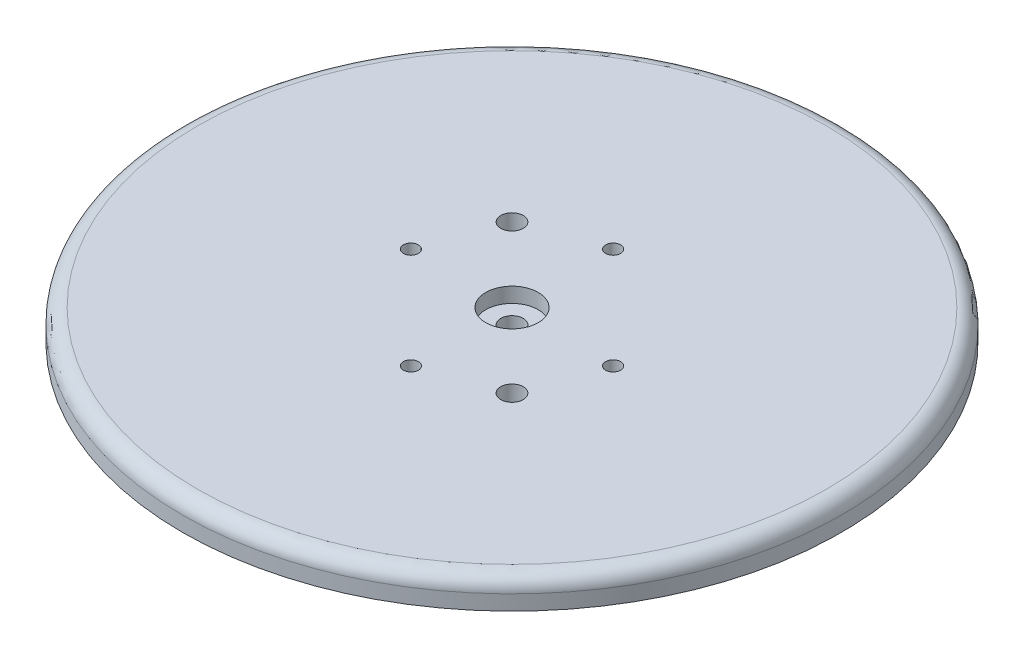
SolidWorks part; units mm, degrees
ref_plane "Front Plane" through (0, 0, 0) normal (0, 0, 1) x (1, 0, 0)
ref_plane "Top Plane" through (0, 0, 0) normal (0, 1, 0) x (1, 0, 0)
ref_plane "Right Plane" through (0, 0, 0) normal (1, 0, 0) x (0, 0, -1)
sketch "Sketch1" plane through (0, 0, 0) normal (0, 1, 0) x (1, 0, 0)
  circle A0 centre (0, 0) radius 44
  dimension "D1" = 88
extrude "Boss-Extrude1" add sketch "Sketch1" along normal blind 4
sketch "Sketch2" plane through (0, 4, 0) normal (0, 1, 0) x (1, 0, 0)
  line L0 (0, -44) -> (0, 44) construction
  line L1 (-44, 0) -> (44, 0) construction
  circle A0 centre (0, 0) radius 44 construction
  circle A1 centre (0, 0) radius 3.5
  dimension "D1" = 7
extrude "Cut-Extrude1" cut sketch "Sketch2" against normal blind 2
sketch "Sketch3" plane through (0, 4, 0) normal (0, 1, 0) x (1, 0, 0)
  line L0 (0, -44) -> (0, 44) construction
  line L1 (-44, 0) -> (44, 0) construction
  circle A0 centre (0, 0) radius 44 construction
  circle A1 centre (0, 13.5) radius 1
  circle A2 centre (0, -13.5) radius 1
  circle A3 centre (-13.5, 0) radius 1
  circle A4 centre (13.5, 0) radius 1
  point P10 (0, 0)
  dimension "D1" = 2
  dimension "D3" = 2
  dimension "D2" = 13.5
  dimension "D4" = 13.5
extrude "Cut-Extrude2" cut sketch "Sketch3" against normal through all
sketch "Sketch5" plane through (0, 2, 0) normal (0, 1, 0) x (1, 0, 0)
  circle A0 centre (0, 0) radius 1.5
  dimension "D1" = 3
extrude "Cut-Extrude3" cut sketch "Sketch5" against normal through all
sketch "Sketch6" plane through (0, 4, 0) normal (0, 1, 0) x (1, 0, 0)
  line L0 (0, -13.5) -> (0, 13.5) construction
  line L1 (-13.5, 0) -> (13.5, 0) construction
  line L2 (0, 0) -> (-13.5, 13.5) construction
  line L3 (0, 0) -> (17.5419, 17.5419) construction
  circle A0 centre (-9.8995, 9.8995) radius 1.5
  circle A1 centre (9.8995, -9.8995) radius 1.5
  dimension "D2" = 3
  dimension "D1" = 45
  dimension "D3" = 14
  dimension "D4" = 90
extrude "Cut-Extrude4" cut sketch "Sketch6" against normal through all
fillet "Fillet1" radius 2 1 edges at (0, 4, 44)
